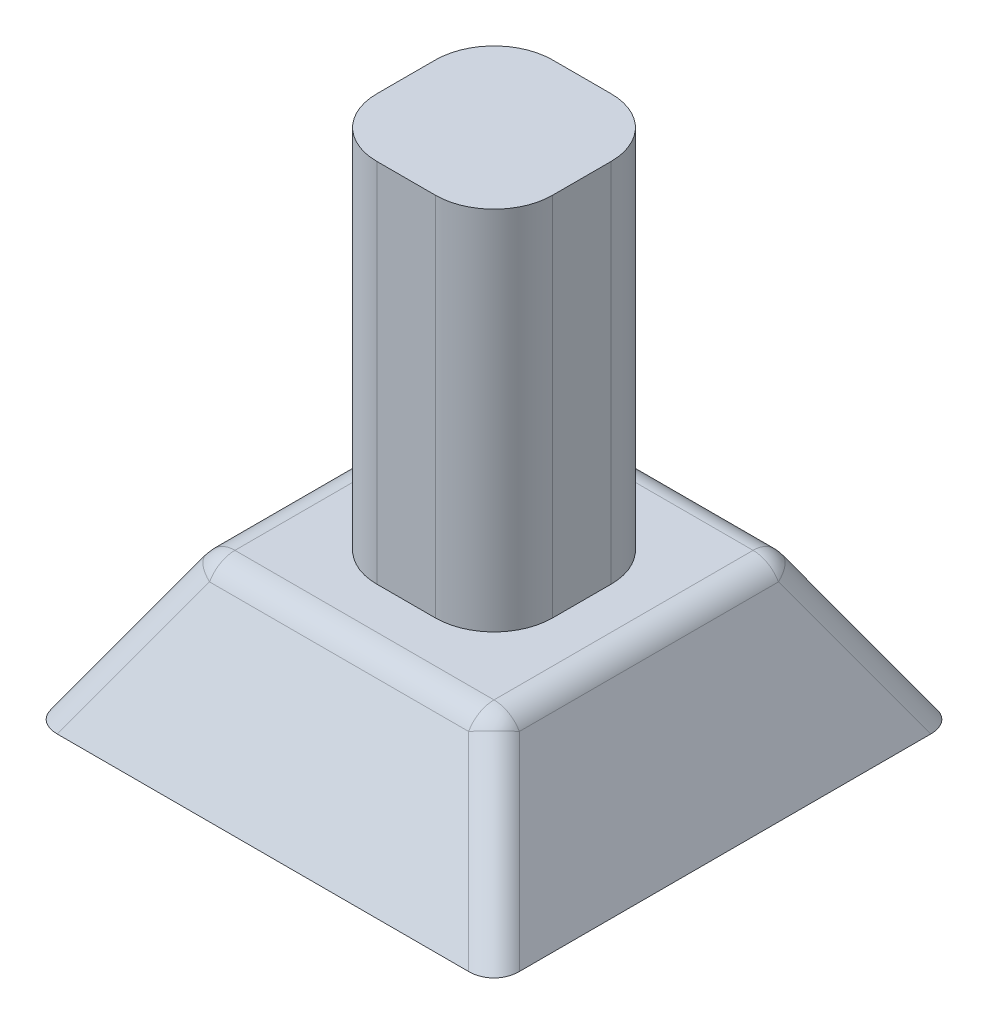
SolidWorks part; units mm, degrees
ref_plane "Front Plane" through (0, 0, 0) normal (0, 0, 1) x (1, 0, 0)
ref_plane "Top Plane" through (0, 0, 0) normal (0, 1, 0) x (1, 0, 0)
ref_plane "Right Plane" through (0, 0, 0) normal (1, 0, 0) x (0, 0, -1)
sketch "Sketch1" plane through (0, 0, 0) normal (0, 1, 0) x (1, 0, 0)
  line L1 (7.62, -7.62) -> (-7.62, -7.62)
  line L2 (7.62, -7.62) -> (7.62, 7.62)
  line L3 (7.62, 7.62) -> (-7.62, 7.62)
  line L4 (-7.62, -7.62) -> (-7.62, 7.62)
  line L5 (7.62, -7.62) -> (-7.62, 7.62) construction
  line L6 (7.62, 7.62) -> (-7.62, -7.62) construction
  point P0 (0, 0)
  dimension "D1" = 15.24
extrude "Boss-Extrude1" add sketch "Sketch1" along normal blind 31.75
fillet "Fillet1" radius 5.08 4 edges at (-7.62, 15.875, 7.62) (7.62, 15.875, 7.62) (7.62, 15.875, -7.62) (-7.62, 15.875, -7.62)
sketch "Sketch2" plane through (0, 0, 0) normal (0, -1, 0) x (1, 0, 0)
  line L1 (12.7, -12.7) -> (-12.7, -12.7)
  line L2 (12.7, -12.7) -> (12.7, 12.7)
  line L3 (12.7, 12.7) -> (-12.7, 12.7)
  line L4 (-12.7, -12.7) -> (-12.7, 12.7)
  line L5 (12.7, -12.7) -> (-12.7, 12.7) construction
  line L6 (12.7, 12.7) -> (-12.7, -12.7) construction
  point P0 (0, 0)
  point P5 (0, 0)
  dimension "D1" = 25.4
extrude "Boss-Extrude3" add sketch "Sketch2" along normal blind 12.7 draft 30 draft outward yes
sketch "Sketch5" plane through (0, -12.7, 0) normal (0, -1, 0) x (1, 0, 0)
  line L8 (-14.9523, 14.9523) -> (-14.9523, -14.9523)
  line L9 (-14.9523, -14.9523) -> (14.9523, -14.9523)
  line L10 (14.9523, -14.9523) -> (14.9523, 14.9523)
  line L11 (14.9523, 14.9523) -> (-14.9523, 14.9523)
  line L12 (-14.9523, 14.9523) -> (-14.9523, -14.9523)
  line L13 (-14.9523, -14.9523) -> (14.9523, -14.9523)
  line L14 (14.9523, -14.9523) -> (14.9523, 14.9523)
  line L15 (14.9523, 14.9523) -> (-14.9523, 14.9523)
  dimension "D1" = 5.08
extrude "Cut-Extrude1" cut sketch "Sketch5" against normal blind 10.16 draft 30
fillet "Fillet2" radius 2.54 8 edges at (-12.7, 0, 0) (0, 0, -12.7) (12.7, 0, 0) (0, 0, 12.7) (-16.3662, -6.35, -16.3662) (16.3662, -6.35, -16.3662) (16.3662, -6.35, 16.3662) (-16.3662, -6.35, 16.3662)
